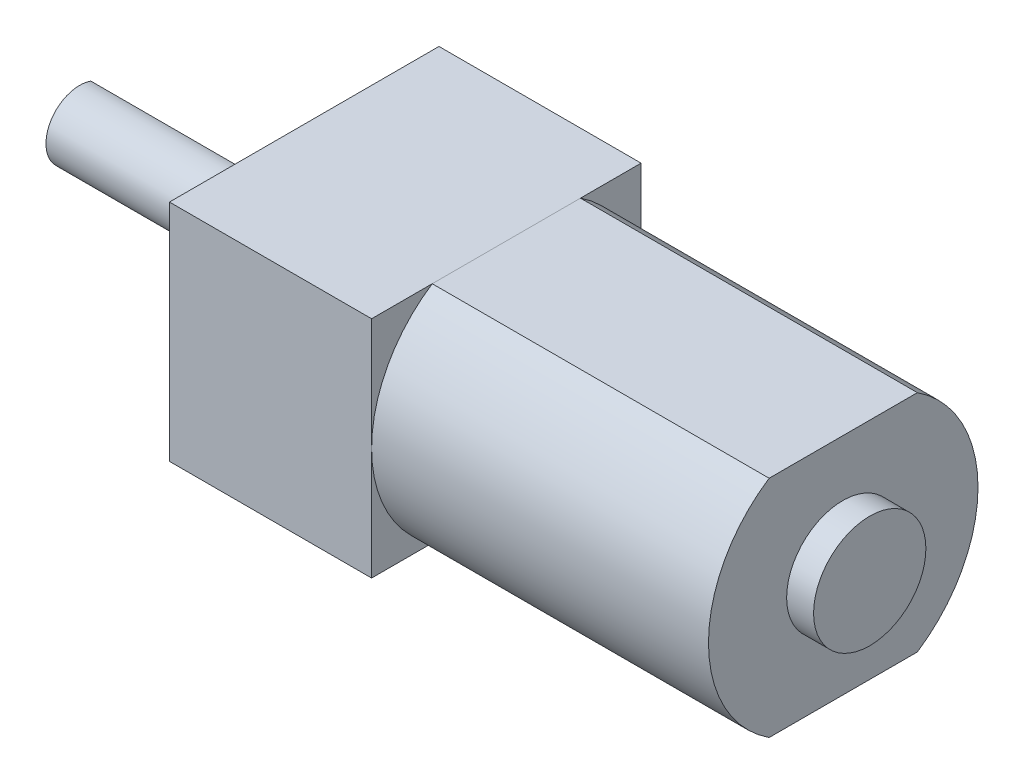
SolidWorks part; units mm, degrees
ref_plane "Front Plane" through (0, 0, 0) normal (0, 0, 1) x (1, 0, 0)
ref_plane "Top Plane" through (0, 0, 0) normal (0, 1, 0) x (1, 0, 0)
ref_plane "Right Plane" through (0, 0, 0) normal (1, 0, 0) x (0, 0, -1)
sketch "Sketch1" plane through (0, 0, 0) normal (1, 0, 0) x (0, 0, -1)
  line L0 (0, 6.1859) -> (0, -7.9167) construction
  line L1 (3.3, 4.0705) -> (-3.3, 4.0705)
  line L3 (-3.3, -5.9295) -> (3.3, -5.9295)
  arc A0 (-3.3, -5.9295) -> (-3.3, 4.0705) centre (-0.0204, -0.9295) cw
  arc A1 (3.3, -5.9295) -> (3.3, 4.0705) centre (0.0204, -0.9295) ccw
  point P3 (0, -0.8654)
  point P5 (-6, -0.9295)
  point P9 (-6, -0.9295)
  point P10 (-3.3, -0.9295)
  point P14 (0, -5.9295)
  point P16 (0, 4.0705)
  dimension "D1" = 10
  dimension "D2" = 3.3
  dimension "D3" = 6
extrude "Boss-Extrude1" add sketch "Sketch1" along normal blind 15 contours L3 A1 L1 A0
ref_plane "Plane1" through (0, -5.9295, 3.3) normal (0, -0.5485, -0.8362) x (-1, 0, 0)
sketch "Sketch2" plane through (0, -5.9295, 3.3) normal (0, -0.5485, -0.8362) x (-1, 0, 0)
  line L0 (0, 0) -> (0, 8.3617) construction
  line L1 (0, 0) -> (0, 8.3617)
sketch "Sketch3" plane through (0, 0, 0) normal (-1, 0, 0) x (0, 0, 1)
  line L0 (6, -0.9295) -> (-6, -0.9295)
  line L1 (-6, -5.9295) -> (-6, 4.0705)
  line L2 (-6, 4.0705) -> (6, 4.0705)
  line L3 (6, 4.0705) -> (6, -5.9295)
  line L4 (-6, -5.9295) -> (6, -5.9295)
  arc A0 (3.3, -5.9295) -> (3.3, 4.0705) centre (0.0204, -0.9295) ccw construction
  arc A1 (-3.3, 4.0705) -> (-3.3, -5.9295) centre (-0.0204, -0.9295) ccw construction
  dimension "D1" = 10
extrude "Boss-Extrude2" add sketch "Sketch3" along normal blind 9 separate body contours L3 L4 L1 L2
ref_plane "Plane2" through (-9, 0, 0) normal (-1, 0, 0) x (0, 0, 1)
sketch "Sketch4" plane through (-9, 0, 0) normal (-1, 0, 0) x (0, 0, 1)
  line L0 (-0.5, -2.3437) -> (-0.5, 0.4847)
  arc A0 (-0.5, -2.3437) -> (-0.5, 0.4847) centre (0, -0.9295) ccw
  dimension "D1" = 3
  dimension "D2" = 0.5
extrude "Boss-Extrude3" add sketch "Sketch4" along normal blind 10 separate body
sketch "Sketch6" plane through (15, 0, 0) normal (1, 0, 0) x (0, 0, -1)
  circle A0 centre (-0.0204, -0.9295) radius 2.5
  dimension "D1" = 5
extrude "Boss-Extrude4" add sketch "Sketch6" along normal blind 1.2
